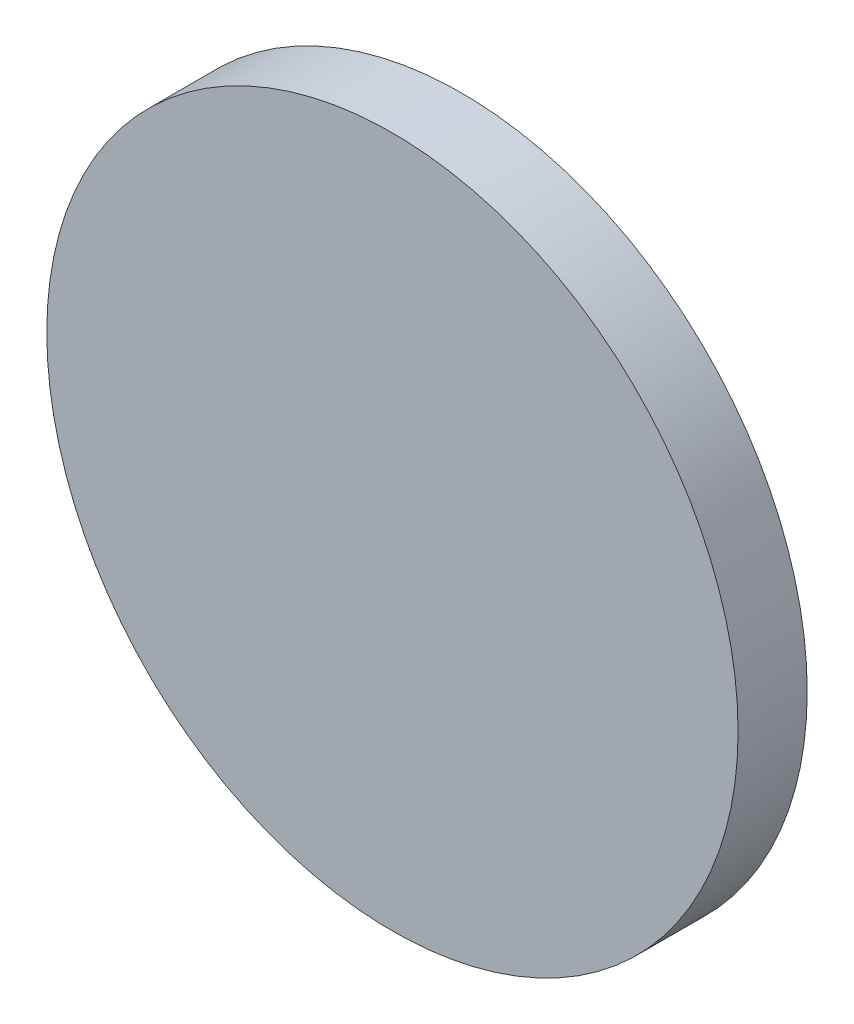
SolidWorks part; units mm, degrees
ref_plane "Plane1" through (0, 0, 0) normal (0, 0, 1) x (1, 0, 0)
ref_plane "Plane2" through (0, 0, 0) normal (0, 1, 0) x (1, 0, 0)
ref_plane "Plane3" through (0, 0, 0) normal (1, 0, 0) x (0, 0, -1)
sketch "Sketch1" plane through (0, 0, 0) normal (0, 0, 1) x (1, 0, 0)
  circle A1 centre (0, 179.95) radius 50
extrude "Base-Extrude" add sketch "Sketch1" against normal blind 10
